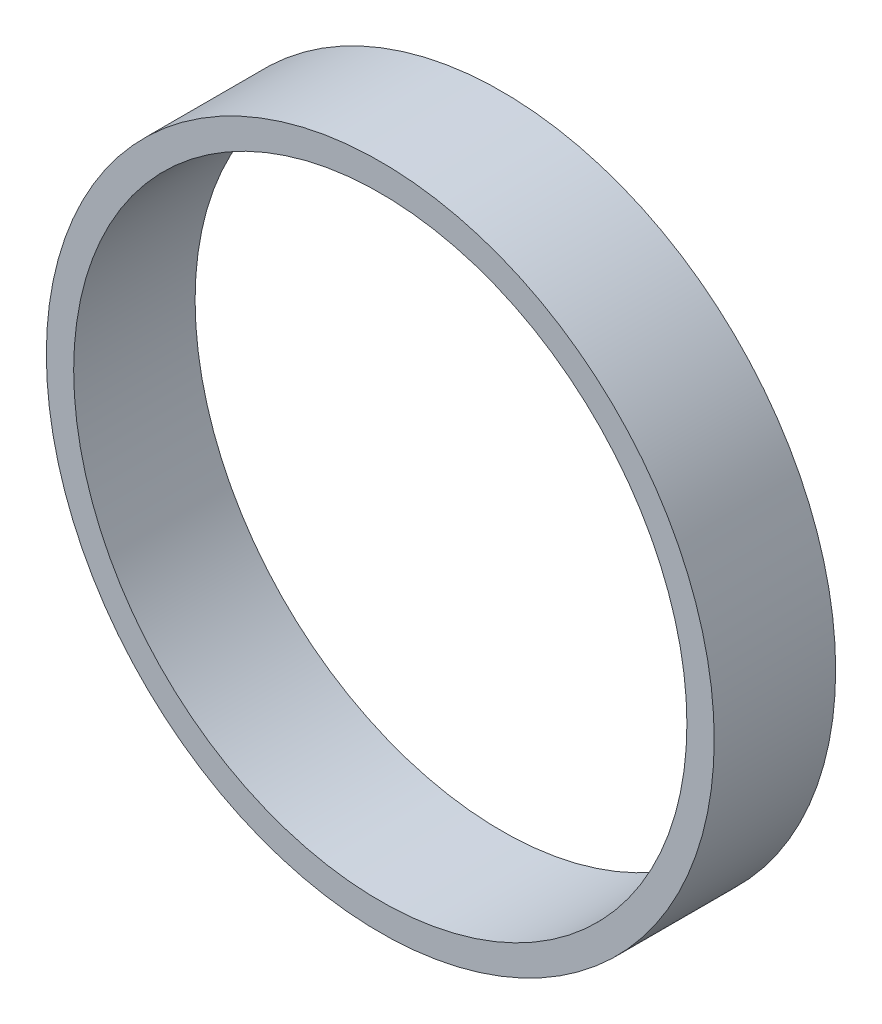
SolidWorks part; units mm, degrees
ref_plane "Płaszczyzna przednia" through (0, 0, 0) normal (0, 0, 1) x (1, 0, 0)
ref_plane "Płaszczyzna górna" through (0, 0, 0) normal (0, 1, 0) x (1, 0, 0)
ref_plane "Płaszczyzna prawa" through (0, 0, 0) normal (1, 0, 0) x (0, 0, -1)
sketch "Szkic1" plane through (0, 0, 0) normal (0, 0, 1) x (1, 0, 0)
  circle A0 centre (0, 0) radius 5.05
  circle A1 centre (0, 0) radius 5.5
  dimension "D1" = 11
  dimension "D2" = 10.1
extrude "Dodanie-wyciągnięcie1" add sketch "Szkic1" along normal blind 2
